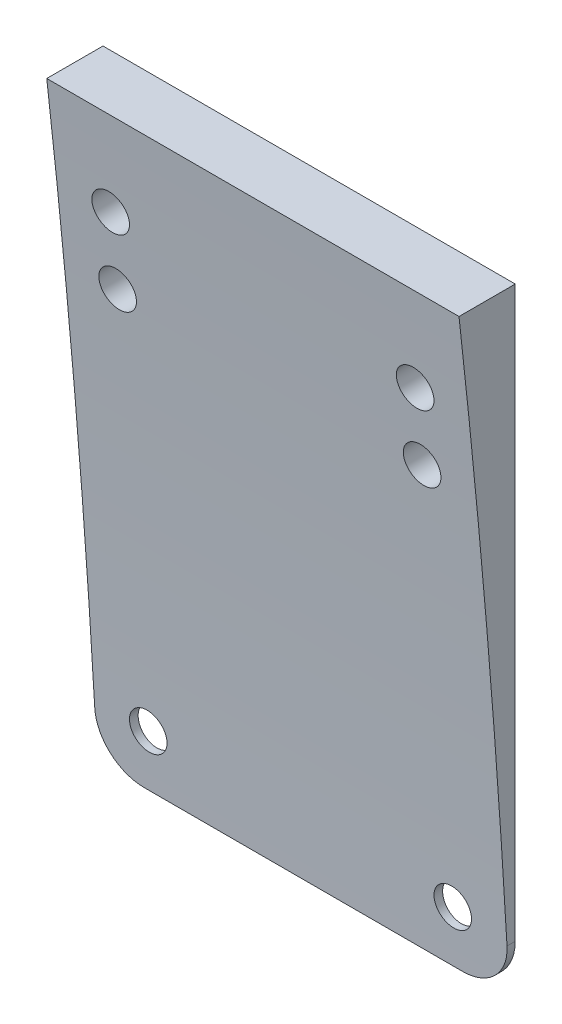
SolidWorks part; units mm, degrees
ref_plane "Front Plane" through (0, 0, 0) normal (0, 0, 1) x (1, 0, 0)
ref_plane "Top Plane" through (0, 0, 0) normal (0, 1, 0) x (1, 0, 0)
ref_plane "Right Plane" through (0, 0, 0) normal (1, 0, 0) x (0, 0, -1)
sketch "Sketch1" plane through (0, 0, 0) normal (0, 0, 1) x (1, 0, 0)
  line L4 (27.94, 49.2125) -> (-27.94, 49.2125)
  line L5 (-27.94, 49.2125) -> (-27.94, -27.94)
  line L6 (-21.59, -34.29) -> (21.59, -34.29)
  line L7 (27.94, -27.94) -> (27.94, 49.2125)
  line L8 (27.94, 49.2125) -> (-27.94, 49.2125)
  line L9 (-27.94, 49.2125) -> (-27.94, -27.94)
  line L10 (-21.59, -34.29) -> (21.59, -34.29)
  line L11 (27.94, -27.94) -> (27.94, 49.2125)
  arc A2 (-27.94, -27.94) -> (-21.59, -34.29) centre (-21.59, -27.94) ccw
  arc A3 (21.59, -34.29) -> (27.94, -27.94) centre (21.59, -27.94) ccw
  arc A4 (-27.94, -27.94) -> (-21.59, -34.29) centre (-21.59, -27.94) ccw
  arc A5 (21.59, -34.29) -> (27.94, -27.94) centre (21.59, -27.94) ccw
  dimension "D1" = 0
extrude "Boss-Extrude1" add sketch "Sketch1" along normal blind 7.62
sketch "Sketch2" plane through (0, 0, 7.62) normal (0, 0, 1) x (1, 0, 0)
  circle A0 centre (-20.6375, 36.5125) radius 2.54 construction
  circle A1 centre (-20.6375, 36.5125) radius 2.54
  circle A2 centre (-20.6375, 26.9875) radius 2.54 construction
  circle A3 centre (-20.6375, 26.9875) radius 2.54
  circle A4 centre (-20.6375, -26.9875) radius 2.54 construction
  circle A5 centre (-20.6375, -26.9875) radius 2.54
  circle A6 centre (20.6375, 36.5125) radius 2.54 construction
  circle A7 centre (20.6375, 36.5125) radius 2.54
  circle A8 centre (20.6375, 26.9875) radius 2.54 construction
  circle A9 centre (20.6375, 26.9875) radius 2.54
  circle A10 centre (20.6375, -26.9875) radius 2.54 construction
  circle A11 centre (20.6375, -26.9875) radius 2.54
extrude "Cut-Extrude1" cut sketch "Sketch2" against normal through all
sketch "Sketch3" plane through (27.94, 0, 0) normal (1, 0, 0) x (0, 0, -1)
  line L0 (0, -34.29) -> (0, -27.94) construction
  line L1 (-7.62, 49.2125) -> (0, 49.2125) construction
  line L2 (0, -27.94) -> (0, 49.2125) construction
  line L3 (-7.62, -34.29) -> (0, -34.29) construction
  line L4 (-7.62, 49.2125) -> (0, 49.2125)
  line L5 (0, -27.94) -> (0, 49.2125)
  line L6 (0, -34.29) -> (0, -27.94)
  line L7 (-7.62, -34.29) -> (0, -34.29)
  line L8 (-7.62, -27.94) -> (-7.62, 49.2125) construction
  line L9 (-7.62, -27.94) -> (-7.62, -34.29) construction
  line L10 (-7.62, -27.94) -> (-7.62, 49.2125)
  line L11 (-7.62, -27.94) -> (-7.62, -34.29)
  arc A0 (-0.762, -34.29) -> (-7.62, 49.2125) centre (-1440.3567, -110.49) ccw
  point P6 (0, 0)
  point P8 (0, 0)
  point P13 (0, 0)
  point P15 (-512.5511, -34.29)
  point P16 (-512.5511, -34.29)
  line M4 (-7.62, 49.2125) -> (-7.62, -27.94)
  line M5 (-7.62, -27.94) -> (0, -27.94)
  dimension "D1" = 0.762
  dimension "D2" = 76.2
extrude "Cut-Extrude2" cut sketch "Sketch3" against normal through all contours A0 M5 M4 | L7 A0 L11 M5
